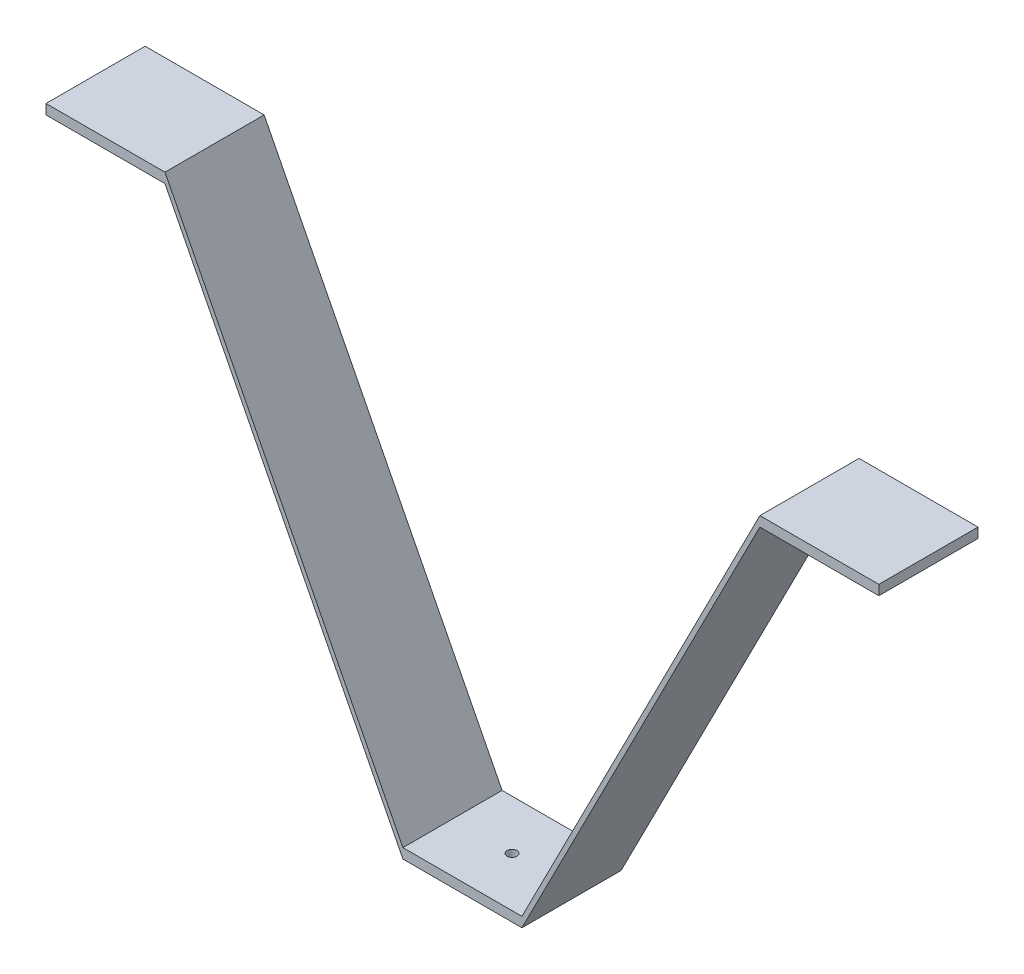
SolidWorks part; units mm, degrees
ref_plane "Front Plane" through (0, 0, 0) normal (0, 0, 1) x (1, 0, 0)
ref_plane "Top Plane" through (0, 0, 0) normal (0, 1, 0) x (1, 0, 0)
ref_plane "Right Plane" through (0, 0, 0) normal (1, 0, 0) x (0, 0, -1)
sketch "Sketch1" plane through (0, 0, 0) normal (0, 1, 0) x (1, 0, 0)
  line L1 (-38.1, -31.75) -> (38.1, -31.75)
  line L2 (-38.1, -31.75) -> (-38.1, 31.75)
  line L3 (-38.1, 31.75) -> (38.1, 31.75)
  line L4 (38.1, -31.75) -> (38.1, 31.75)
  line L5 (-38.1, -31.75) -> (38.1, 31.75) construction
  line L6 (-38.1, 31.75) -> (38.1, -31.75) construction
  point P0 (0, 0)
  dimension "D1" = 76.2
  dimension "D2" = 63.5
extrude "Boss-Extrude1" add sketch "Sketch1" along normal blind 6.35
sketch "Sketch2" plane through (0, 6.35, 0) normal (0, 1, 0) x (1, 0, 0)
  circle A0 centre (0, 0) radius 3.175
  dimension "D1" = 6.35
extrude "Cut-Extrude1" cut sketch "Sketch2" against normal through all
ref_plane "Plane1" through (190.5, 0, 0) normal (1, 0, 0) x (0, 0, -1)
sketch "Sketch3" plane through (0, 0, 31.75) normal (0, 0, 1) x (1, 0, 0)
  line L0 (38.1, 6.35) -> (190.5, 304.8)
  line L1 (38.1, 0) -> (190.5, 298.45)
  line L2 (190.5, -3.4925) -> (190.5, 3.4925) construction
  line L3 (-38.1, 0) -> (38.1, 0) construction
  line L4 (38.1, 6.35) -> (38.1, 0)
  line L5 (190.5, 304.8) -> (190.5, 298.45)
  dimension "D1" = 304.8
extrude "Boss-Extrude2" add sketch "Sketch3" against normal blind 63.5
sketch "Sketch4" plane through (190.5, 0, 0) normal (1, 0, 0) x (0, 0, -1)
  line L1 (-31.75, 304.8) -> (31.75, 304.8)
  line L2 (-31.75, 304.8) -> (-31.75, 298.45)
  line L3 (-31.75, 298.45) -> (31.75, 298.45)
  line L4 (31.75, 304.8) -> (31.75, 298.45)
extrude "Boss-Extrude3" add sketch "Sketch4" along normal blind 76.2
mirror "Mirror1" about plane through (0, 0, 0) normal (1, 0, 0) of "Boss-Extrude3", "Boss-Extrude2"
